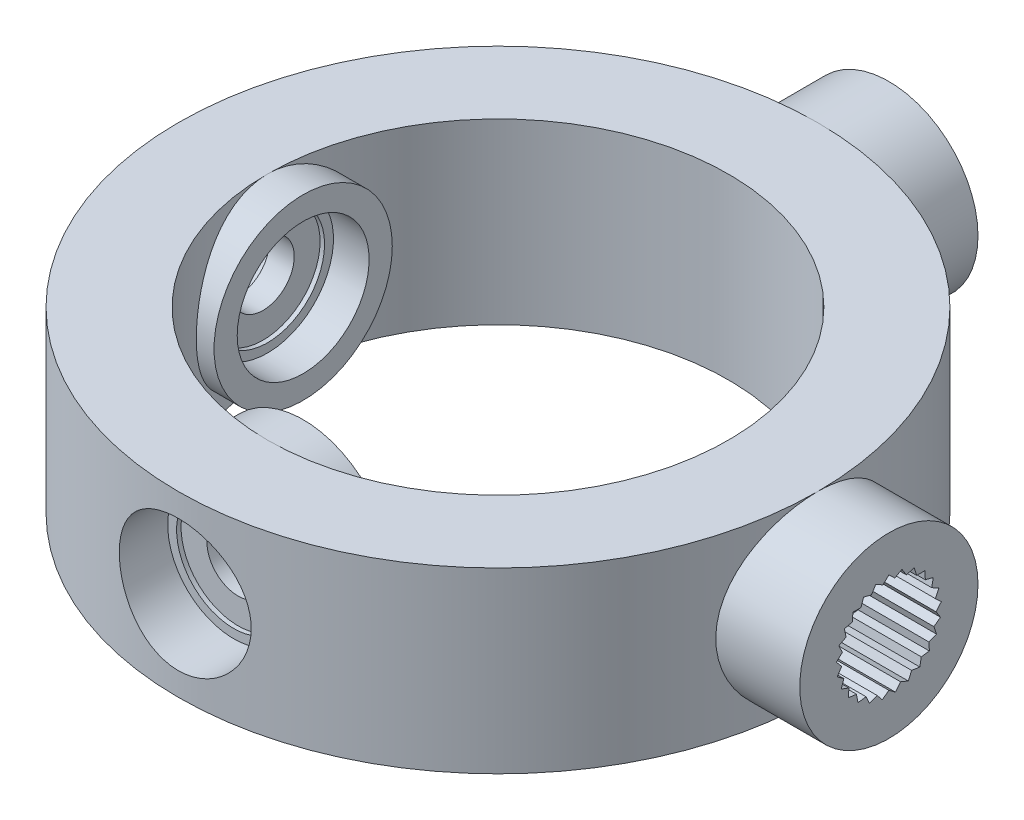
SolidWorks part; units mm, degrees
ref_plane "Front Plane" through (0, 0, 0) normal (0, 0, 1) x (1, 0, 0)
ref_plane "Top Plane" through (0, 0, 0) normal (0, 1, 0) x (1, 0, 0)
ref_plane "Right Plane" through (0, 0, 0) normal (1, 0, 0) x (0, 0, -1)
sketch "Sketch1" plane through (0, 0, 0) normal (0, 1, 0) x (1, 0, 0)
  circle A0 centre (0, 0) radius 17.9289
  dimension "D1" = 35.8579
extrude "Boss-Extrude1" add sketch "Sketch1" along normal blind 10 contours A0
sketch "Sketch2" plane through (0, 10, 0) normal (0, 1, 0) x (1, 0, 0)
  circle A2 centre (0, 0) radius 12.9289
  circle A3 centre (0, 0) radius 12.9289
  dimension "D1" = 5
extrude "Cut-Extrude1" cut sketch "Sketch2" against normal through all
sketch "Sketch3" plane through (0, 0, 0) normal (0, 0, 1) x (1, 0, 0)
  line L0 (0, 0) -> (0, 10) construction
  line L1 (-17.9289, 0) -> (17.9289, 0) construction
  line L2 (12.9289, 10) -> (-12.9289, 10) construction
  line L3 (0, 5) -> (17.9289, 5) construction
  line L4 (17.9289, 0) -> (17.9289, 10) construction
  line L5 (0, 5) -> (-17.9289, 5) construction
  line L6 (-17.9289, 10) -> (-17.9289, 0) construction
  line L7 (17.9289, 5) -> (21.9289, 5) construction
  dimension "D1" = 4
ref_plane "Plane1" through (21.9289, 0, 0) normal (1, 0, 0) x (0, 0, -1)
sketch "Sketch4" plane through (21.9289, 0, 0) normal (1, 0, 0) x (0, 0, -1)
  line L0 (0, 0) -> (0, 10) construction
  line L1 (17.9289, 10) -> (-17.9289, 10) construction
  circle A0 centre (0, 5) radius 5
extrude "Boss-Extrude2" add sketch "Sketch4" against normal up to surface (4.7113 mm away)
ref_plane "Plane2" through (-17.9289, 0, 0) normal (1, 0, 0) x (0, 0, -1)
ref_plane "Plane3" through (-10.9289, 0, 0) normal (1, 0, 0) x (0, 0, -1)
sketch "Sketch7" plane through (-10.9289, 0, 0) normal (1, 0, 0) x (0, 0, -1)
  line L0 (12.9289, 10) -> (-12.9289, 10) construction
  circle A0 centre (0, 5) radius 5
extrude "Boss-Extrude4" add sketch "Sketch7" against normal up to surface (0.994 mm away)
sketch "Sketch8" plane through (-17.9289, 0, 0) normal (1, 0, 0) x (0, 0, -1)
  circle A0 centre (0, 5) radius 1.75
  dimension "D1" = 3.5
extrude "Cut-Extrude3" cut sketch "Sketch8" along normal up to surface (7 mm away) up to face at (-10.9289, 5, -5)
sketch "Sketch10" plane through (0, 0, 0) normal (1, 0, 0) x (0, 0, -1)
  line L0 (0, 0) -> (0, 10) construction
  line L1 (0, 5) -> (-17.9289, 5) construction
  line L2 (-17.9289, 10) -> (-17.9289, 0) construction
  line L3 (0, 5) -> (17.9289, 5) construction
  line L4 (17.9289, 5) -> (21.9289, 5) construction
  circle A0 centre (0, 5) radius 5 construction
  dimension "D1" = 4
ref_plane "Plane4" through (0, 0, -21.9289) normal (0, 0, 1) x (1, 0, 0)
sketch "Sketch11" plane through (0, 0, -21.9289) normal (0, 0, 1) x (1, 0, 0)
  line L0 (17.9289, 10) -> (-17.9289, 10) construction
  circle A0 centre (0, 5) radius 5
extrude "Boss-Extrude5" add sketch "Sketch11" along normal up to surface (4.7113 mm away)
ref_plane "Plane5" through (0, 0, 17.9289) normal (0, 0, 1) x (1, 0, 0)
ref_plane "Plane6" through (0, 0, 10.9289) normal (0, 0, 1) x (1, 0, 0)
sketch "Sketch12" plane through (0, 0, 10.9289) normal (0, 0, 1) x (1, 0, 0)
  line L0 (12.9289, 10) -> (-12.9289, 10) construction
  circle A0 centre (0, 5) radius 5
extrude "Boss-Extrude6" add sketch "Sketch12" along normal up to surface (0.9941 mm away)
sketch "Sketch13" plane through (0, 0, 17.9289) normal (0, 0, 1) x (1, 0, 0)
  circle A0 centre (0, 5) radius 1.75
  dimension "D1" = 3.5
extrude "Cut-Extrude4" cut sketch "Sketch13" against normal up to surface (7 mm away) up to face at (5, 5, 10.9289)
sketch "Sketch14" plane through (0, 0, -21.9289) normal (0, 0, -1) x (-1, 0, 0)
  line L0 (0, 5) -> (0, 7.95) construction
  line L1 (0, 5) -> (0.3697, 7.9267) construction
  line L2 (0, 5) -> (-0.3697, 7.9267) construction
  line L3 (0, 7.95) -> (-0.3327, 7.6339)
  line L4 (0, 7.95) -> (0.3327, 7.6339)
  line L5 (0.7336, 7.8573) -> (0.3327, 7.6339)
  line L6 (0.7336, 7.8573) -> (0.9773, 7.4684)
  line L7 (1.4212, 7.5851) -> (0.9773, 7.4684)
  line L8 (1.4212, 7.5851) -> (1.5605, 7.1478)
  line L9 (2.0194, 7.1505) -> (1.5605, 7.1478)
  line L10 (2.0194, 7.1505) -> (2.0456, 6.6923)
  line L11 (2.4908, 6.5807) -> (2.0456, 6.6923)
  line L12 (2.4908, 6.5807) -> (2.4022, 6.1304)
  line L13 (2.8056, 5.9116) -> (2.4022, 6.1304)
  line L14 (2.8056, 5.9116) -> (2.6078, 5.4975)
  line L15 (2.9442, 5.1852) -> (2.6078, 5.4975)
  line L16 (2.9442, 5.1852) -> (2.6496, 4.8333)
  line L17 (2.8977, 4.4472) -> (2.6496, 4.8333)
  line L18 (2.8977, 4.4472) -> (2.5249, 4.1796)
  line L19 (2.6692, 3.744) -> (2.5249, 4.1796)
  line L20 (2.6692, 3.744) -> (2.2416, 3.5775)
  line L21 (2.273, 3.1196) -> (2.2416, 3.5775)
  line L22 (2.273, 3.1196) -> (1.8174, 3.0647)
  line L23 (1.734, 2.6134) -> (1.8174, 3.0647)
  line L24 (1.734, 2.6134) -> (1.279, 2.6735)
  line L25 (1.086, 2.2572) -> (1.279, 2.6735)
  line L26 (1.086, 2.2572) -> (0.6602, 2.4286)
  line L27 (0.3697, 2.0733) -> (0.6602, 2.4286)
  line L28 (0.3697, 2.0733) -> (0, 2.3452)
  line L29 (-0.3697, 2.0733) -> (0, 2.3452)
  line L30 (-0.3697, 2.0733) -> (-0.6602, 2.4286)
  line L31 (-1.086, 2.2572) -> (-0.6602, 2.4286)
  line L32 (-1.086, 2.2572) -> (-1.279, 2.6735)
  line L33 (-1.734, 2.6134) -> (-1.279, 2.6735)
  line L34 (-1.734, 2.6134) -> (-1.8174, 3.0647)
  line L35 (-2.273, 3.1196) -> (-1.8174, 3.0647)
  line L36 (-2.273, 3.1196) -> (-2.2416, 3.5775)
  line L37 (-2.6692, 3.744) -> (-2.2416, 3.5775)
  line L38 (-2.6692, 3.744) -> (-2.5249, 4.1796)
  line L39 (-2.8977, 4.4472) -> (-2.5249, 4.1796)
  line L40 (-2.8977, 4.4472) -> (-2.6496, 4.8333)
  line L41 (-2.9442, 5.1852) -> (-2.6496, 4.8333)
  line L42 (-2.9442, 5.1852) -> (-2.6078, 5.4975)
  line L43 (-2.8056, 5.9116) -> (-2.6078, 5.4975)
  line L44 (-2.8056, 5.9116) -> (-2.4022, 6.1304)
  line L45 (-2.4908, 6.5807) -> (-2.4022, 6.1304)
  line L46 (-2.4908, 6.5807) -> (-2.0456, 6.6923)
  line L47 (-2.0194, 7.1505) -> (-2.0456, 6.6923)
  line L48 (-2.0194, 7.1505) -> (-1.5605, 7.1478)
  line L49 (-1.4212, 7.5851) -> (-1.5605, 7.1478)
  line L50 (-1.4212, 7.5851) -> (-0.9773, 7.4684)
  line L51 (-0.7336, 7.8573) -> (-0.9773, 7.4684)
  line L52 (-0.7336, 7.8573) -> (-0.3327, 7.6339)
  circle A0 centre (0, 5) radius 2.95 construction
  point P19 (0, 5)
  point P83 (0, 5)
  dimension "D1" = 5.9
  dimension "D2" = 14.4
  dimension "D3" = 7.2
  dimension "D4" = 53.67
  dimension "D5" = 53.67
  dimension "D6" = 25
extrude "Cut-Extrude5" cut sketch "Sketch14" against normal blind 4
pattern_circular "CirPattern1" count 2 over 270 about axis through (0, 0, 0) along (0, 1, 0) of "Cut-Extrude5"
sketch "Sketch15" plane through (0, 0, 17.9289) normal (0, 0, 1) x (1, 0, 0)
  circle A0 centre (0, 5) radius 3.7
  dimension "D1" = 7.4
extrude "Cut-Extrude6" cut sketch "Sketch15" against normal blind 3.1
sketch "Sketch16" plane through (0, 0, 10.9289) normal (0, 0, 1) x (1, 0, 0)
  circle A0 centre (0, 5) radius 3.7
  dimension "D1" = 7.4
extrude "Cut-Extrude7" cut sketch "Sketch16" along normal blind 2
sketch "Sketch17" plane through (0, 0, 14.8289) normal (0, 0, 1) x (1, 0, 0)
  circle A0 centre (0, 5) radius 3.2
  circle A1 centre (0, 5) radius 3.7 construction
  circle A2 centre (0, 5) radius 3.7
  circle M2 centre (0, 5) radius 1.75
  dimension "D1" = 6.4
extrude "Cut-Extrude8" cut sketch "Sketch17" against normal blind 0.25 contours A0 M2
sketch "Sketch18" plane through (0, 0, 12.9289) normal (0, 0, -1) x (-1, 0, 0)
  circle A0 centre (0, 5) radius 3.2
  circle A1 centre (0, 5) radius 3.7 construction
  circle A2 centre (0, 5) radius 3.7
  circle M3 centre (0, 5) radius 1.75
  dimension "D1" = 6.4
extrude "Cut-Extrude9" cut sketch "Sketch18" against normal blind 0.25 contours A0 M3
pattern_circular "CirPattern2" count 2 over 90 about axis through (0, 10, 0) along (0, 1, 0) of "Cut-Extrude9", "Cut-Extrude8", "Cut-Extrude6", "Cut-Extrude7"
